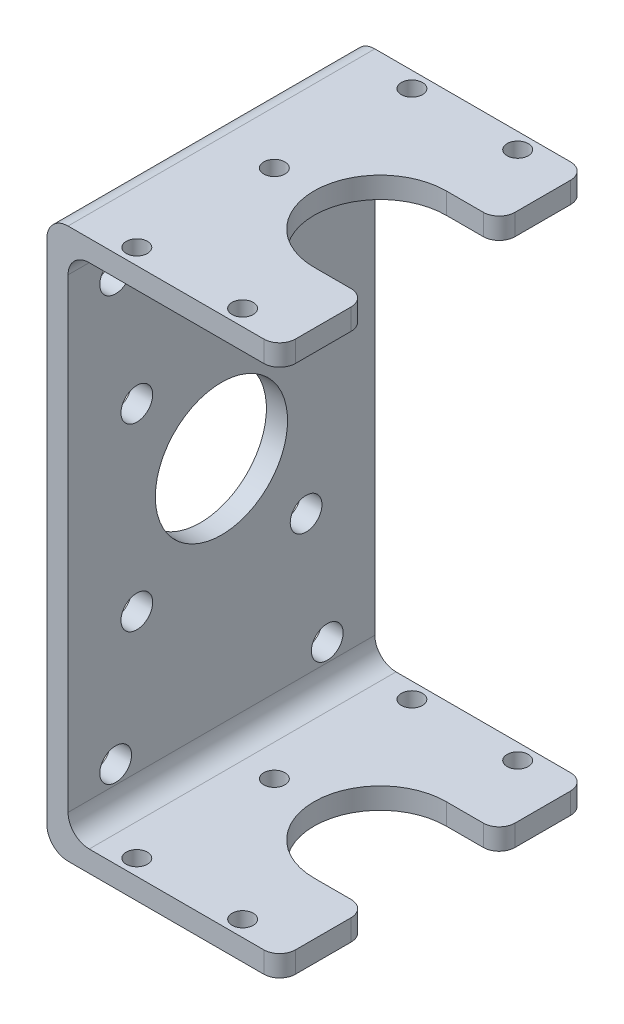
SolidWorks part; units mm, degrees
ref_plane "正面" through (0, 0, 0) normal (0, 0, 1) x (1, 0, 0)
ref_plane "平面" through (0, 0, 0) normal (0, 1, 0) x (1, 0, 0)
ref_plane "右側面" through (0, 0, 0) normal (1, 0, 0) x (0, 0, -1)
sketch "ｽｹｯﾁ1" plane through (0, 0, 0) normal (0, 0, 1) x (1, 0, 0)
  line L0 (0, 26.2989) -> (0, -25.7011)
  line L1 (0, -25.7011) -> (22, -25.7011)
  line L2 (22, -25.7011) -> (22, -23.7011)
  line L3 (22, -23.7011) -> (2, -23.7011)
  line L4 (2, -23.7011) -> (2, 24.2989)
  line L5 (2, 24.2989) -> (22, 24.2989)
  line L6 (22, 24.2989) -> (22, 26.2989)
  line L7 (22, 26.2989) -> (0, 26.2989)
  dimension "D1" = 52
  dimension "D2" = 48
  dimension "D3" = 2
  dimension "D4" = 2
  dimension "D5" = 22
  dimension "D6" = 20
  dimension "D7" = 20
  dimension "D8" = 22
extrude "ﾎﾞｽ - 押し出し1" add sketch "ｽｹｯﾁ1" along normal mid plane 29
sketch "ｽｹｯﾁ2" plane through (0, 26.2989, 0) normal (0, 1, 0) x (1, 0, 0)
  line L0 (22, -14.5) -> (22, 14.5) construction
  line L1 (-12.1, 0) -> (12.1, 0) construction
  line L2 (22, -14.5) -> (0, -14.5) construction
  line L3 (17, 6.25) -> (17, -6.25)
  line L4 (17, -6.25) -> (22, -6.25)
  line L5 (22, -6.25) -> (22, 6.25)
  line L6 (22, 6.25) -> (17, 6.25)
  circle A0 centre (17, 0) radius 6.25
  circle A1 centre (17, 13) radius 1
  circle A2 centre (17, -13) radius 1
  circle A5 centre (7, 0) radius 1
  circle A6 centre (7, 13) radius 1
  circle A7 centre (7, -13) radius 1
  line M5 (22, -14.5) -> (22, 14.5)
  dimension "D1" = 12.5
  dimension "D3" = 2
  dimension "D5" = 2
  dimension "D2" = 5
  dimension "D6" = 10
  dimension "D7" = 14.5
  dimension "D8" = 13
  dimension "D9" = 14.5
  dimension "D4" = 0
  dimension "D10" = 2
extrude "ｶｯﾄ - 押し出し1" cut sketch "ｽｹｯﾁ2" against normal blind 30 contours L3 A0 L5 | A0 L4 M5 | A0 L6 M5 | L3 A0
sketch "ｽｹｯﾁ3" plane through (0, -25.7011, 0) normal (0, -1, 0) x (1, 0, 0)
  line L0 (22, 14.5) -> (22, -14.5) construction
  line L1 (12.1, 0) -> (-12.1, 0) construction
  line L2 (0, 14.5) -> (22, 14.5) construction
  line L3 (17, -6.25) -> (17, 6.25)
  line L4 (17, 6.25) -> (22, 6.25)
  line L5 (22, 6.25) -> (22, -6.25)
  line L6 (22, -6.25) -> (17, -6.25)
  line L7 (0, -14.5) -> (22, -14.5) construction
  circle A0 centre (17, 0) radius 6.25
  circle A1 centre (17, -13) radius 1
  circle A2 centre (17, 13) radius 1
  circle A5 centre (7, 0) radius 1
  circle A6 centre (7, -13) radius 1
  circle A7 centre (7, 13) radius 1
  point P10 (0, 0)
  point P12 (0, 0)
  line M5 (22, -14.5) -> (22, 14.5)
  dimension "D1" = 12.5
  dimension "D3" = 2
  dimension "D6" = 2
  dimension "D2" = 5
  dimension "D4" = 13
  dimension "D7" = 10
  dimension "D8" = 14.5
  dimension "D9" = 0
  dimension "D10" = 14.5
  dimension "D5" = 2
extrude "ｶｯﾄ - 押し出し2" cut sketch "ｽｹｯﾁ3" against normal blind 30 contours A6 | A1 | L3 A0 | L5 A0 L3 | A0 L4 M5 | A2 | A5
fillet "ﾌｨﾚｯﾄ1" radius 2 4 edges at (2, 24.2989, 0) (2, -23.7011, 0) (0, -25.7011, 0) (0, 26.2989, 0)
fillet "ﾌｨﾚｯﾄ2" radius 1.5 8 edges at (22, -24.7011, -14.5) (22, -24.7011, -6.25) (22, -24.7011, 6.25) (22, -24.7011, 14.5) (22, 25.2989, -14.5) (22, 25.2989, -6.25) (22, 25.2989, 6.25) (22, 25.2989, 14.5)
sketch "ｽｹｯﾁ4" plane through (0, 0, 0) normal (-1, 0, 0) x (0, 0, 1)
  line L0 (14.5, 24.2989) -> (14.5, -23.7011) construction
  line L2 (0, -12.1) -> (0, 12.1) construction
  line L3 (12.1, 0) -> (-12.1, 0) construction
  circle A0 centre (0, 0) radius 6.25
  circle A1 centre (10, -20) radius 1.5
  circle A2 centre (-10, -20) radius 1.5
  circle A3 centre (-10, 20) radius 1.5
  circle A4 centre (10, 20) radius 1.5
  circle A5 centre (8, -8.5) radius 1.5
  circle A6 centre (-8, -8.5) radius 1.5
  circle A7 centre (-8, 8.5) radius 1.5
  circle A8 centre (8, 8.5) radius 1.5
  dimension "D1" = 12.5
  dimension "D2" = 3
  dimension "D5" = 3
  dimension "D3" = 4.5
  dimension "D4" = 20
  dimension "D6" = 8.5
  dimension "D7" = 6.5
extrude "ｶｯﾄ - 押し出し3" cut sketch "ｽｹｯﾁ4" against normal blind 30
